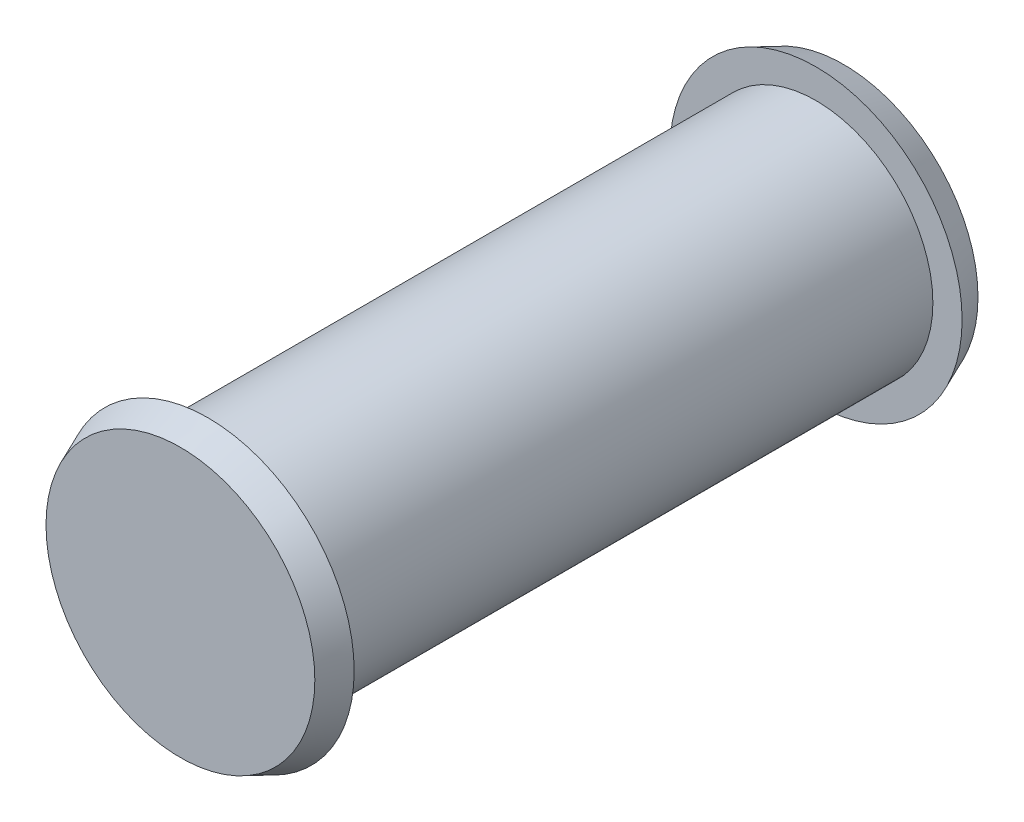
SolidWorks part; units mm, degrees
ref_plane "Front" through (0, 0, 0) normal (0, 0, 1) x (1, 0, 0)
ref_plane "Top" through (0, 0, 0) normal (0, 1, 0) x (1, 0, 0)
ref_plane "Right" through (0, 0, 0) normal (1, 0, 0) x (0, 0, -1)
other "Configuration Table"
sketch "Sketch1" plane through (0, 0, 0) normal (0, 0, 1) x (1, 0, 0)
  circle A0 centre (-108.0823, 104.7845) radius 2.54 construction
  circle A1 centre (-108.0823, 104.7845) radius 2.54
extrude "Extrude1" add sketch "Sketch1" against normal up to surface (13.208 mm away)
sketch "Sketch2" plane through (0, 0, 0) normal (0, 0, 1) x (1, 0, 0)
  circle A0 centre (-108.0823, 104.7845) radius 3.175
  dimension "D1" = 6.35
extrude "Extrude2" add sketch "Sketch2" along normal blind 0.6 draft 23
sketch "Sketch3" plane through (-216.0398, 1.1371, -13.208) normal (0, 0, -1) x (-1, 0, 0)
  circle A0 centre (-107.9575, 103.6473) radius 3.175
  dimension "D1" = 6.35
extrude "Extrude3" add sketch "Sketch3" along normal blind 0.6 draft 23
